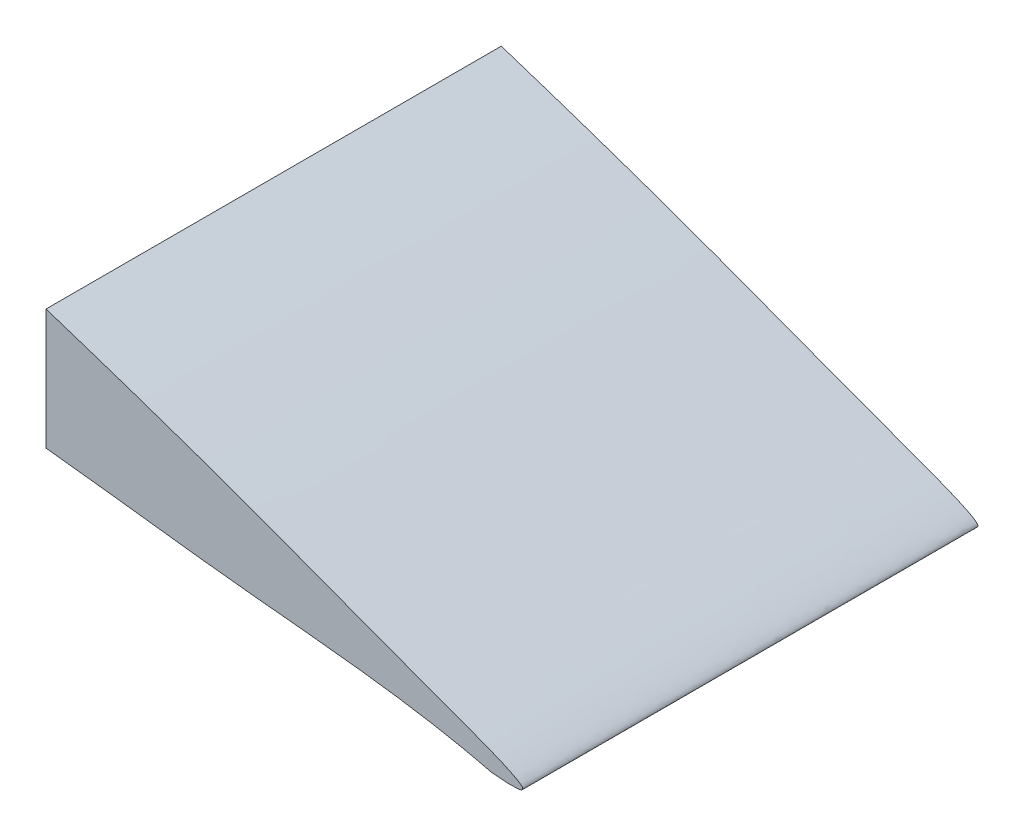
SolidWorks part; units mm, degrees
ref_plane "Front Plane" through (0, 0, 0) normal (0, 0, 1) x (1, 0, 0)
ref_plane "Top Plane" through (0, 0, 0) normal (0, 1, 0) x (1, 0, 0)
ref_plane "Right Plane" through (0, 0, 0) normal (1, 0, 0) x (0, 0, -1)
sketch "Sketch1" plane through (0, 0, 0) normal (0, 0, 1) x (1, 0, 0)
  spline S0 degree 3 poles (0.0006, 0.0001) (0.8106, 7.3592) (8.6491, 17.8566) (26.2867, 29.9752) (52.1111, 42.0692) (89.5976, 49.2908) (131.4008, 47.8848) (173.2567, 40.0411) (217.9611, 29.613) (256.9521, 19.5289) (290.3598, 8.711) (301.2732, 4.3828) (314.8169, -0.5162) (309.8463, 0.0001) knots 0 0 0 0 0.060864 0.113688 0.188609 0.312909 0.448482 0.557612 0.691544 0.852438 0.929756 0.976058 1 1 1 1
  spline S1 degree 3 poles (309.8463, 0.0001) (303.9568, 1.471) (293.9895, 2.094) (276.264, 4.5144) (260.8463, 5.4274) (235.8588, 7.8703) (205.1014, 8.8381) (157.7186, 9.0307) (110.4973, 6.1815) (66.5062, -0.5867) (36.4547, -6.0985) (15.3166, -6.1891) (1.2307, -6.9241) (0.0006, 0.0001) knots 0 0 0 0 0.057787 0.095275 0.171021 0.205339 0.335319 0.464904 0.658702 0.785512 0.893517 0.943092 1 1 1 1
extrude "Boss-Extrude1" add sketch "Sketch1" along normal blind 31.1531
sketch "Sketch2" plane through (0, 0, 31.1531) normal (0, 0, 1) x (1, 0, 0)
  circle A0 centre (20.32, 10.16) radius 6.35
  circle A1 centre (227.2963, 19.0501) radius 3.175
  dimension "D2" = 12.7
  dimension "D3" = 6.35
  dimension "D6" = 20.32
  dimension "D1" = 82.55
  dimension "D4" = 19.05
  dimension "D5" = 10.16
extrude "Cut-Extrude1" cut sketch "Sketch2" against normal through all
sketch "Sketch4" plane through (0, 0, 31.1531) normal (0, 0, 1) x (1, 0, 0)
  line L1 (279.4, -24.2166) -> (-32.1124, -24.2166)
  line L2 (279.4, -24.2166) -> (279.4, 93.2727)
  line L3 (279.4, 93.2727) -> (-32.1124, 93.2727)
  line L4 (-32.1124, -24.2166) -> (-32.1124, 93.2727)
  dimension "D1" = 279.4
extrude "Cut-Extrude3" cut sketch "Sketch4" against normal through all
